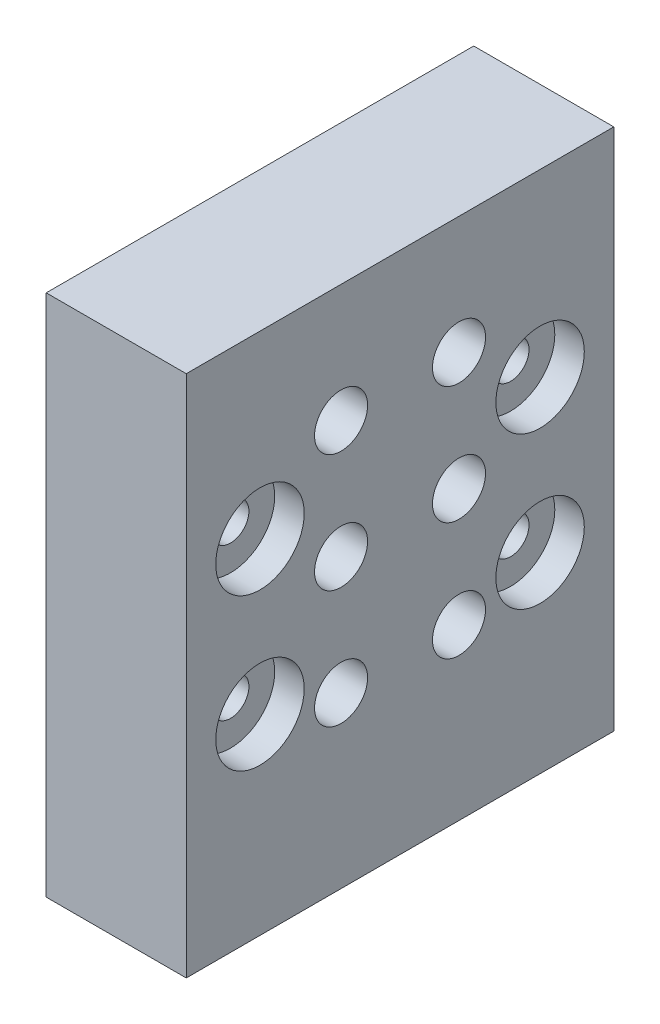
SolidWorks part; units mm, degrees
ref_plane "前基準面" through (0, 0, 0) normal (0, 0, 1) x (1, 0, 0)
ref_plane "上基準面" through (0, 0, 0) normal (0, 1, 0) x (1, 0, 0)
ref_plane "右基準面" through (0, 0, 0) normal (1, 0, 0) x (0, 0, -1)
sketch "草圖1" plane through (0, 0, 0) normal (1, 0, 0) x (0, 0, -1)
  line L1 (0, 0) -> (25, 0)
  line L2 (0, 0) -> (0, 31.5)
  line L3 (0, 31.5) -> (25, 31.5)
  line L4 (25, 0) -> (25, 31.5)
  dimension "D1" = 25
  dimension "D2" = 31.5
extrude "填料-伸長1" add sketch "草圖1" along normal blind 2
sketch "草圖2" plane through (2, 0, 0) normal (1, 0, 0) x (0, 0, -1)
  circle A0 centre (22, 21.3) radius 1.25
  circle A1 centre (22, 11) radius 1.25
  circle A2 centre (3, 21.3) radius 1.25
  circle A3 centre (3, 11) radius 1.25
  dimension "D3" = 2.5
  dimension "D4" = 2.5
  dimension "D5" = 2.5
  dimension "D7" = 2.5
extrude "除料-伸長1" cut sketch "草圖2" against normal blind 5
sketch "草圖3" plane through (0, 0, 0) normal (0, 0, 1) x (1, 0, 0)
  line L1 (0, 31.5) -> (2, 31.5)
  line L2 (0, 31.5) -> (0, 0)
  line L3 (0, 0) -> (2, 0)
  line L4 (2, 31.5) -> (2, 0)
extrude "填料-伸長2" add sketch "草圖3" along normal blind 2
sketch "草圖4" plane through (0, 0, -25) normal (0, 0, -1) x (-1, 0, 0)
  line L1 (-2, 31.5) -> (0, 31.5)
  line L2 (-2, 31.5) -> (-2, 0)
  line L3 (-2, 0) -> (0, 0)
  line L4 (0, 31.5) -> (0, 0)
extrude "填料-伸長3" add sketch "草圖4" along normal blind 2
sketch "草圖5" plane through (0, 0, 0) normal (-1, 0, 0) x (0, 0, 1)
  line L0 (2, 0) -> (-27, 0) construction
  line L1 (-27, 31.5) -> (-25, 31.5)
  line L2 (-27, 31.5) -> (-27, 0)
  line L3 (-27, 0) -> (-25, 0)
  line L4 (-25, 31.5) -> (-25, 0)
  dimension "D1" = 2
extrude "填料-伸長4" add sketch "草圖5" along normal blind 2
sketch "草圖6" plane through (0, 0, 0) normal (-1, 0, 0) x (0, 0, 1)
  line L1 (2, 31.5) -> (0, 31.5)
  line L2 (2, 31.5) -> (2, 0)
  line L3 (2, 0) -> (0, 0)
  line L4 (0, 31.5) -> (0, 0)
extrude "填料-伸長5" add sketch "草圖6" along normal blind 2
sketch "草圖7" plane through (0, 31.5, 0) normal (0, 1, 0) x (1, 0, 0)
  line L1 (-2, 27) -> (2, 27)
  line L2 (-2, 27) -> (-2, -2)
  line L3 (-2, -2) -> (2, -2)
  line L4 (2, 27) -> (2, -2)
extrude "填料-伸長6" add sketch "草圖7" along normal blind 2
sketch "草圖8" plane through (0, 0, 0) normal (0, -1, 0) x (-1, 0, 0)
  line L1 (-2, -2) -> (2, -2)
  line L2 (-2, -2) -> (-2, 27)
  line L3 (-2, 27) -> (2, 27)
  line L4 (2, -2) -> (2, 27)
extrude "填料-伸長7" add sketch "草圖8" along normal blind 2
sketch "草圖9" plane through (2, 0, 0) normal (1, 0, 0) x (0, 0, -1)
  line L1 (-2, 33.5) -> (27, 33.5)
  line L2 (-2, 33.5) -> (-2, -2)
  line L3 (-2, -2) -> (27, -2)
  line L4 (27, 33.5) -> (27, -2)
  circle A0 centre (3, 21.3) radius 1.25
  circle A1 centre (22, 21.3) radius 1.25
  circle A2 centre (22, 11) radius 1.25
  circle A3 centre (3, 11) radius 1.25
extrude "填料-伸長8" add sketch "草圖9" along normal blind 3
sketch "草圖11" plane through (5, 0, 0) normal (1, 0, 0) x (0, 0, -1)
  line L1 (-2, 33.5) -> (27, 33.5)
  line L2 (-2, 33.5) -> (-2, -2)
  line L3 (-2, -2) -> (27, -2)
  line L4 (27, 33.5) -> (27, -2)
  circle A0 centre (3, 21.3) radius 1.25
  circle A1 centre (22, 21.3) radius 1.25
  circle A2 centre (22, 11) radius 1.25
  circle A3 centre (3, 11) radius 1.25
extrude "填料-伸長9" add sketch "草圖11" along normal blind 2.5
sketch "草圖12" plane through (7.5, 0, 0) normal (1, 0, 0) x (0, 0, -1)
  circle A0 centre (8.5, 25.5) radius 1.8
  circle A1 centre (16.5, 25.5) radius 1.8
  circle A2 centre (16.5, 17.5) radius 1.8
  circle A3 centre (16.5, 9.5) radius 1.8
  circle A4 centre (8.5, 9.5) radius 1.8
  circle A5 centre (8.5, 17.5) radius 1.8
  dimension "D1" = 3.6
  dimension "D2" = 3.6
  dimension "D3" = 3.6
  dimension "D4" = 3.6
  dimension "D5" = 3.6
  dimension "D6" = 3.6
extrude "除料-伸長2" cut sketch "草圖12" against normal blind 13.5
sketch "草圖13" plane through (7.5, 0, 0) normal (1, 0, 0) x (0, 0, -1)
  circle A7 centre (3, 21.3) radius 3
  circle A8 centre (3, 11) radius 3
  circle A9 centre (22, 11) radius 3
  circle A10 centre (22, 21.3) radius 3
extrude "除料-伸長3" cut sketch "草圖13" against normal blind 2
